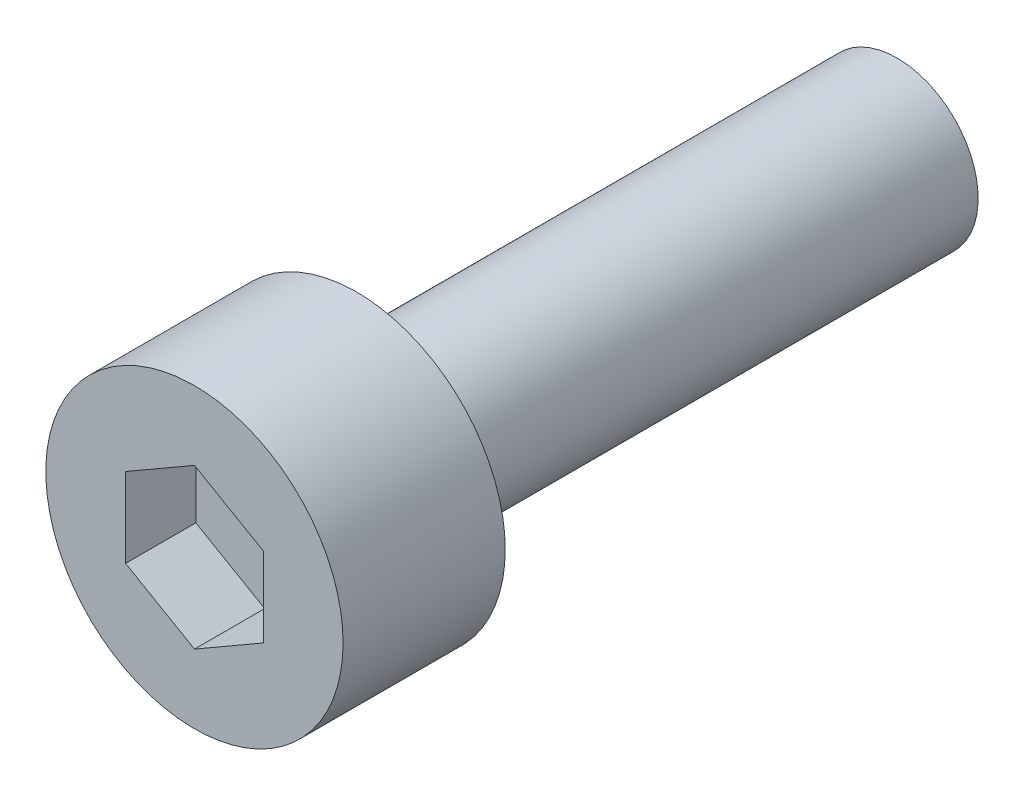
SolidWorks part; units mm, degrees
material "AISI 304"
ref_plane "Front Plane" through (0, 0, 0) normal (0, 0, 1) x (1, 0, 0)
ref_plane "Top Plane" through (0, 0, 0) normal (0, 1, 0) x (1, 0, 0)
ref_plane "Right Plane" through (0, 0, 0) normal (1, 0, 0) x (0, 0, -1)
sketch "草图1" plane through (0, 0, 0) normal (0, 0, 1) x (1, 0, 0)
  circle A0 centre (0, 0) radius 2.75
  dimension "D1" = 5.5
extrude "凸台-拉伸1" add sketch "草图1" along normal blind 3
sketch "草图2" plane through (0, 0, 3) normal (0, 0, 1) x (1, 0, 0)
  line L1 (1.275, -0.7361) -> (1.275, 0.7361)
  line L2 (1.275, 0.7361) -> (0, 1.4722)
  line L3 (0, 1.4722) -> (-1.275, 0.7361)
  line L4 (-1.275, 0.7361) -> (-1.275, -0.7361)
  line L5 (-1.275, -0.7361) -> (0, -1.4722)
  line L6 (0, -1.4722) -> (1.275, -0.7361)
  circle A0 centre (0, 0) radius 1.275 construction
  dimension "D1" = 2.55
extrude "切除-拉伸1" cut sketch "草图2" against normal blind 1.3
sketch "草图3" plane through (0, 0, 0) normal (0, 0, -1) x (-1, 0, 0)
  circle A0 centre (0, 0) radius 1.5
  dimension "D1" = 3
extrude "凸台-拉伸2" add sketch "草图3" along normal blind 10
cosmetic thread "装饰螺纹线1" parameters "D2"=3
